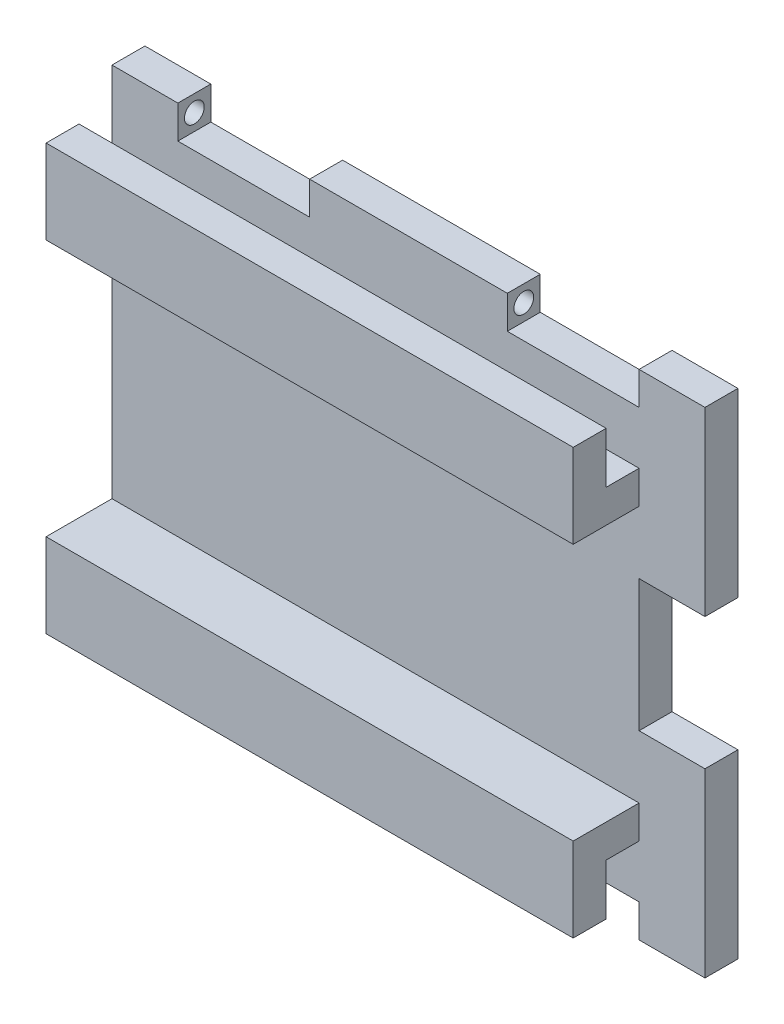
SolidWorks part; units mm, degrees
material "Alliage 1060"
ref_plane "Plan de dessus" through (0, 0, 0) normal (0, 0, 1) x (1, 0, 0)
ref_plane "Plan de droite" through (0, 0, 0) normal (0, 1, 0) x (1, 0, 0)
ref_plane "Plan de face" through (0, 0, 0) normal (1, 0, 0) x (0, 0, -1)
sketch "Esquisse1" plane through (0, 0, 0) normal (0, 0, 1) x (1, 0, 0)
  line L0 (90, 47.5) -> (80, 47.5)
  line L1 (0, 0) -> (10, 0)
  line L2 (0, 0) -> (0, 75)
  line L3 (0, 75) -> (10, 75)
  line L4 (90, 0) -> (90, 27.5)
  line L5 (80, 47.5) -> (80, 27.5)
  line L6 (80, 27.5) -> (90, 27.5)
  line L7 (90, 47.5) -> (90, 75)
  line L8 (80, 0) -> (90, 0)
  line L10 (80, 0) -> (80, 5)
  line L11 (80, 5) -> (60, 5)
  line L12 (60, 0) -> (60, 5)
  line L14 (30, 0) -> (30, 5)
  line L15 (30, 5) -> (10, 5)
  line L16 (10, 0) -> (10, 5)
  line L17 (30, 0) -> (60, 0)
  line L18 (30, 75) -> (60, 75)
  line L20 (80, 75) -> (80, 70)
  line L21 (80, 70) -> (60, 70)
  line L22 (60, 75) -> (60, 70)
  line L24 (10, 75) -> (10, 70)
  line L25 (10, 70) -> (30, 70)
  line L26 (30, 75) -> (30, 70)
  line L27 (80, 75) -> (90, 75)
  dimension "D1" = 90
  dimension "D2" = 75
  dimension "D3" = 10
  dimension "D4" = 20
  dimension "D5" = 20
  dimension "D6" = 5
  dimension "D7" = 20
  dimension "D8" = 5
  dimension "D9" = 10
  dimension "D10" = 10
  dimension "D11" = 5
  dimension "D12" = 5
  dimension "D13" = 10
  dimension "D14" = 10
  dimension "D15" = 20
  dimension "D16" = 20
extrude "Boss.-Extru.1" add sketch "Esquisse1" along normal blind 5
sketch "Esquisse3" plane through (0, 0, 0) normal (-1, 0, 0) x (0, 0, 1)
  line L0 (5, 18) -> (15, 18)
  line L1 (5, 75) -> (5, 0) construction
  line L2 (15, 18) -> (15, 5.25)
  line L8 (10, 5.25) -> (10, 13)
  line L9 (10, 13) -> (5, 13)
  line L10 (5, 13) -> (5, 18)
  line L11 (5, 37.5) -> (43.0923, 37.5) construction
  line L12 (5, 0) -> (0, 0) construction
  line L13 (5, 62) -> (5, 57)
  line L14 (10, 62) -> (5, 62)
  line L15 (10, 69.75) -> (10, 62)
  line L20 (15, 69.75) -> (10, 69.75)
  line L21 (15, 57) -> (15, 69.75)
  line L22 (5, 57) -> (15, 57)
  line L23 (15, 5.25) -> (10, 5.25)
  point P6 (14, 6.4675)
  dimension "D1" = 13
  dimension "D2" = 5
  dimension "D3" = 10
  dimension "D4" = 5
  dimension "D8" = 12.75
extrude "Boss.-Extru.2" add sketch "Esquisse3" against normal offset from surface (80 mm away) 10 up to face at (90, 13.75, 2.5)
sketch "Esquisse5" plane through (0, 0, 0) normal (-1, 0, 0) x (0, 0, 1)
  line L0 (5, 13) -> (5, 0) construction
  line L3 (5, 0) -> (0, 0) construction
  line L4 (5, 75) -> (5, 62) construction
  line L6 (5, 75) -> (0, 75) construction
  circle A0 centre (2.5, 2.5) radius 1.5
  circle A1 centre (2.5, 72.5) radius 1.5
  dimension "D1" = 2.5
  dimension "D3" = 3
  dimension "D4" = 3
  dimension "D2" = 2.5
  dimension "D5" = 2.5
  dimension "D6" = 2.5
extrude "Enlèv. mat.-Extru.1" cut sketch "Esquisse5" against normal offset from surface (85 mm away) 5 up to face at (90, 13.75, 2.5)
